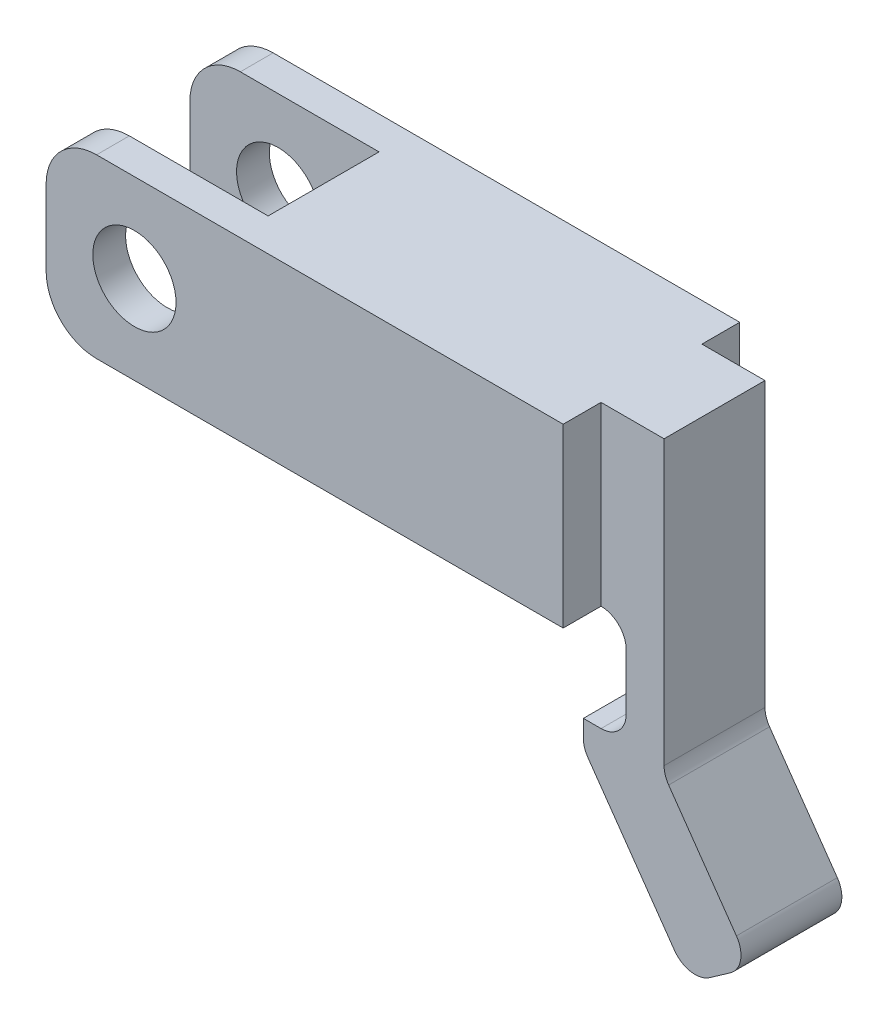
SolidWorks part; units mm, degrees
ref_plane "Front Plane" through (0, 0, 0) normal (0, 0, 1) x (1, 0, 0)
ref_plane "Top Plane" through (0, 0, 0) normal (0, 1, 0) x (1, 0, 0)
ref_plane "Right Plane" through (0, 0, 0) normal (1, 0, 0) x (0, 0, -1)
sketch "Sketch1" plane through (0, 0, 0) normal (0, 0, 1) x (1, 0, 0)
  line L1 (-6.5, 3.5) -> (6.5, 3.5)
  line L2 (-6.5, 3.5) -> (-6.5, -3.5)
  line L3 (-6.5, -3.5) -> (6.5, -3.5)
  line L4 (6.5, 3.5) -> (6.5, -3.5)
  line L5 (-6.5, 3.5) -> (6.5, -3.5) construction
  line L6 (-6.5, -3.5) -> (6.5, 3.5) construction
  point P0 (0, 0)
  dimension "D1" = 13
  dimension "D2" = 7
extrude "Boss-Extrude1" add sketch "Sketch1" along normal mid plane 7
sketch "Sketch2" plane through (0, 0, 3.5) normal (0, 0, 1) x (1, 0, 0)
  line L0 (-6.5, -3.5) -> (6.5, -3.5) construction
  arc A0 (-0.75, -3.5) -> (0.75, -3.5) centre (0, -3.5) cw
  dimension "D1" = 0.75
extrude "Cut-Extrude1" [suppressed] cut sketch "Sketch2" against normal through all and the other way through all flip side to cut
pattern_linear "LPattern1" [suppressed] count 3 spacing 3.5 count 3 spacing 3.5
fillet "Fillet1" [suppressed] radius 0.5
sketch "Sketch3" plane through (0, 0, 3.5) normal (0, 0, 1) x (1, 0, 0)
  line L1 (-6.5, 3.5) -> (-14, 3.5)
  line L2 (-6.5, 3.5) -> (-6.5, -3.5)
  line L3 (-6.5, -3.5) -> (-14, -3.5)
  line L4 (-14, 3.5) -> (-14, -3.5)
  line L5 (-6.5, 3.5) -> (-6.5, -3.5) construction
  line L6 (6.5, 3.5) -> (-6.5, 3.5) construction
  line L8 (-6.5, -3.5) -> (6.5, -3.5) construction
  dimension "D1" = 7.5
extrude "Boss-Extrude2" add sketch "Sketch3" against normal blind 1.3
sketch "Sketch4" plane through (0, 0, 3.5) normal (0, 0, 1) x (1, 0, 0)
  circle A2 centre (-10.5, 0) radius 1.65
  circle A3 centre (-10.5, 0) radius 1.65
  dimension "D1" = 0
extrude "Cut-Extrude2" cut sketch "Sketch4" against normal up to next
mirror "Mirror1" about plane through (0, 0, 0) normal (0, 0, 1) of "Cut-Extrude2", "Boss-Extrude2"
fillet "Fillet3" radius 0.7 1 edges at (-6.5, -3.5, 0)
fillet "Fillet4" radius 2 4 edges at (-14, -3.5, 2.85) (-14, -3.5, -2.85) (-14, 3.5, -2.85) (-14, 3.5, 2.85)
ref_plane "Plane1" through (7.5, 0, 0) normal (1, 0, 0) x (0, 0, -1)
sketch "Sketch6" plane through (0, 0, 0) normal (0, 0, 1) x (1, 0, 0)
  line L0 (6.5, 3.5) -> (9, 3.5)
  line L1 (9, 3.5) -> (9, -8.0397)
  line L2 (9, -8.0397) -> (12.4415, -12.9546)
  line L3 (12.4415, -12.9546) -> (9.984, -14.6754)
  line L4 (9.984, -14.6754) -> (5.8, -8.7)
  line L5 (5.8, -8.7) -> (5.8, -7.7)
  line L6 (5.8, -7.7) -> (7.5, -7.7)
  line L7 (7.5, -7.7) -> (7.5, -3.5)
  line L8 (7.5, -3.5) -> (6.5, -3.5)
  line L9 (6.5, -3.5) -> (6.5, 3.5) construction
  line L10 (6.5, -3.5) -> (6.5, 3.5)
  line L11 (-12, -3.5) -> (6.5, -3.5) construction
  line L12 (7, -5.7142) -> (7, -6.8929) construction
  line L13 (5.5, -11.1) -> (5.5, -7.6) construction
  line L14 (5.5, -7.6) -> (6.2929, -7.6) construction
  dimension "D1" = 0.5
  dimension "D2" = 0.3
  dimension "D3" = 0.1
  dimension "D4" = 6
  dimension "D5" = 3
  dimension "D6" = 1.5
  dimension "D7" = 1
  dimension "D8" = 145
extrude "Boss-Extrude4" add sketch "Sketch6" along normal mid plane 4
fillet "Fillet5" radius 1 6 edges at (7.5, -3.5, 0) (7.5, -7.7, 0) (5.8, -8.7, 0) (9.984, -14.6754, 0) (12.4415, -12.9546, 0) (9, -8.0397, 0)
